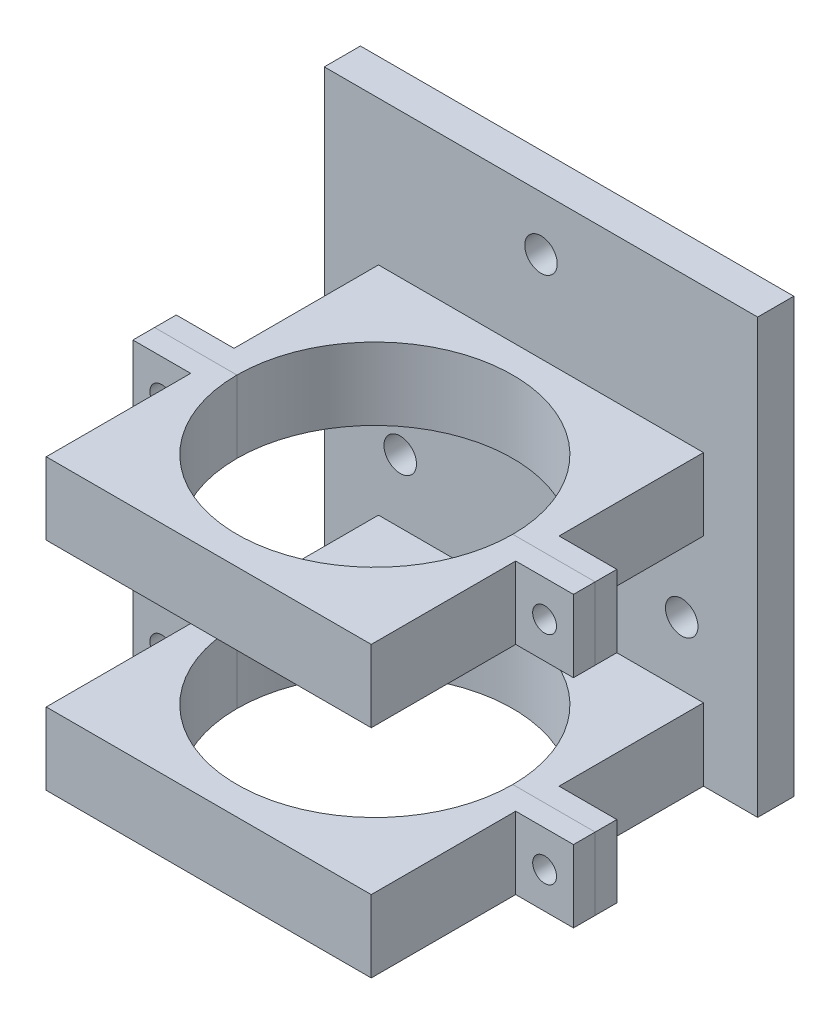
SolidWorks part; units mm, degrees
ref_plane "正面" through (0, 0, 0) normal (0, 0, 1) x (1, 0, 0)
ref_plane "平面" through (0, 0, 0) normal (0, 1, 0) x (1, 0, 0)
ref_plane "右側面" through (0, 0, 0) normal (1, 0, 0) x (0, 0, -1)
sketch "ｽｹｯﾁ1" plane through (0, 0, 0) normal (0, 0, 1) x (1, 0, 0)
  line L1 (-30, -30) -> (30, -30)
  line L2 (-30, -30) -> (-30, 30)
  line L3 (-30, 30) -> (30, 30)
  line L4 (30, -30) -> (30, 30)
  line L5 (-30, -30) -> (30, 30) construction
  line L6 (-30, 30) -> (30, -30) construction
  point P0 (0, 0)
  dimension "D1" = 60
extrude "ﾎﾞｽ - 押し出し1" add sketch "ｽｹｯﾁ1" along normal blind 5
sketch "ｽｹｯﾁ2" plane through (0, 0, 5) normal (0, 0, 1) x (1, 0, 0)
  line L0 (30, 0) -> (-30, 0) construction
  line L1 (30, -30) -> (30, 30) construction
  line L2 (-30, 30) -> (-30, -30) construction
  line L3 (0, -30) -> (0, 30) construction
  line L4 (-30, -30) -> (30, -30) construction
  line L5 (30, 30) -> (-30, 30) construction
  circle A0 centre (0, 22.5) radius 2.25
  circle A1 centre (19.4856, -11.25) radius 2.25
  circle A2 centre (-19.4856, -11.25) radius 2.25
  point P21 (0, 0)
  dimension "D2" = 4.5
  dimension "D1" = 22.5
  dimension "D3" = 3
extrude "ｶｯﾄ - 押し出し1" cut sketch "ｽｹｯﾁ2" against normal through all
sketch "ｽｹｯﾁ3" plane through (0, -30, 0) normal (0, -1, 0) x (1, 0, 0)
  line L0 (22.5, 5) -> (-22.5, 5)
  line L1 (-30, 5) -> (30, 5) construction
  line L2 (-22.5, 5) -> (-22.5, 25)
  line L3 (-22.5, 25) -> (-30.5, 25)
  line L4 (-30.5, 25) -> (-30.5, 31)
  line L5 (-30.5, 31) -> (-22.5, 31)
  line L6 (-22.5, 31) -> (-22.5, 51)
  line L7 (-22.5, 51) -> (22.5, 51)
  line L8 (0, 51) -> (0, 5) construction
  line L9 (22.5, 5) -> (22.5, 25)
  line L10 (22.5, 25) -> (30.5, 25)
  line L11 (30.5, 25) -> (30.5, 31)
  line L12 (30.5, 31) -> (22.5, 31)
  line L13 (22.5, 31) -> (22.5, 51)
  dimension "D1" = 20
  dimension "D2" = 22.5
  dimension "D3" = 20
  dimension "D4" = 6
  dimension "D5" = 8
extrude "ﾎﾞｽ - 押し出し2" add sketch "ｽｹｯﾁ3" against normal blind 10
ref_plane "平面1" through (0, 0, 0) normal (0, 1, 0) x (1, 0, 0)
sketch "ｽｹｯﾁ4" plane through (0, 0, 0) normal (0, 1, 0) x (1, 0, 0)
  line L0 (-22.5, -51) -> (22.5, -51)
  line L1 (22.5, -51) -> (-22.5, -51) construction
  line L2 (22.5, -51) -> (22.5, -31)
  line L3 (22.5, -31) -> (30.5, -31)
  line L4 (30.5, -31) -> (30.5, -25)
  line L5 (30.5, -25) -> (22.5, -25)
  line L6 (22.5, -25) -> (22.5, -5)
  line L7 (22.5, -5) -> (-22.5, -5)
  line L8 (30, -5) -> (-30, -5) construction
  line L9 (0, -5) -> (0, -51) construction
  line L10 (-22.5, -51) -> (-22.5, -31)
  line L11 (-22.5, -31) -> (-30.5, -31)
  line L12 (-30.5, -31) -> (-30.5, -25)
  line L13 (-30.5, -25) -> (-22.5, -25)
  line L14 (-22.5, -25) -> (-22.5, -5)
extrude "ﾎﾞｽ - 押し出し3" add sketch "ｽｹｯﾁ4" along normal blind 10
sketch "ｽｹｯﾁ5" plane through (0, 10, 0) normal (0, 1, 0) x (1, 0, 0)
  line L0 (30.5, -28) -> (-30.5, -28) construction
  line L1 (30.5, -31) -> (30.5, -25) construction
  line L2 (-30.5, -25) -> (-30.5, -31) construction
  circle A0 centre (0, -28) radius 19.1
  dimension "D1" = 38.2
extrude "ｶｯﾄ - 押し出し2" cut sketch "ｽｹｯﾁ5" against normal through all
ref_plane "平面2" through (0, 0, 28) normal (0, 0, 1) x (1, 0, 0)
sketch "ｽｹｯﾁ7" plane through (0, 0, 31) normal (0, 0, 1) x (1, 0, 0)
  line L0 (-26.5, 10) -> (-26.5, -30) construction
  line L1 (-30.5, 10) -> (-22.5, 10) construction
  line L2 (-22.5, -30) -> (-30.5, -30) construction
  line L3 (26.5, 10) -> (26.5, -30) construction
  line L4 (22.5, 10) -> (30.5, 10) construction
  line L5 (30.5, -30) -> (22.5, -30) construction
  line L6 (30.5, 5) -> (-30.5, 5) construction
  line L7 (30.5, 10) -> (30.5, 0) construction
  line L8 (-30.5, 10) -> (-30.5, 0) construction
  line L9 (30.5, -25) -> (-30.5, -25) construction
  line L10 (30.5, -20) -> (30.5, -30) construction
  line L11 (-30.5, -20) -> (-30.5, -30) construction
  circle A0 centre (-26.5, 5) radius 1.65
  circle A1 centre (26.5, 5) radius 1.65
  circle A2 centre (26.5, -25) radius 1.65
  circle A3 centre (-26.5, -25) radius 1.65
  dimension "D1" = 3.3
extrude "ｶｯﾄ - 押し出し3" cut sketch "ｽｹｯﾁ7" against normal up to next
split "部品分割1" trim tools "平面2" bodies to split 106 resulting bodies 107 108 109
